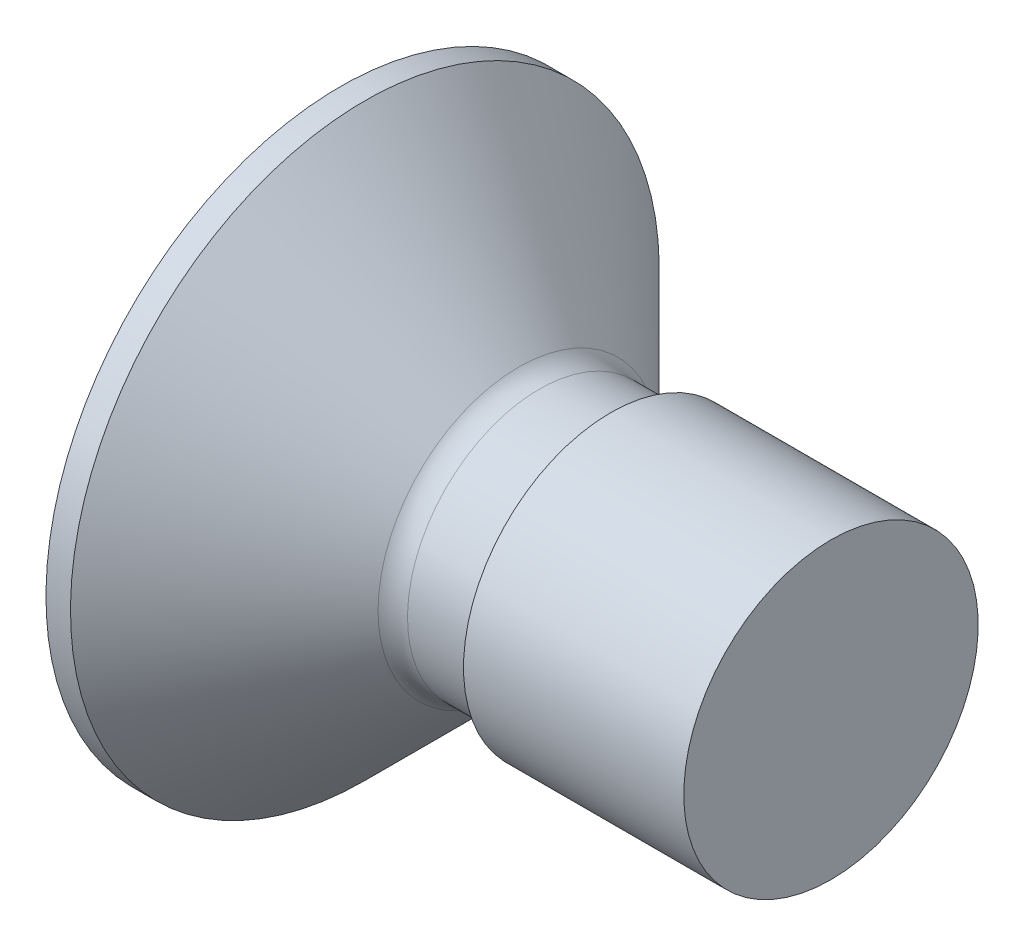
SolidWorks part; units mm, degrees
material "SUS304相当"
ref_plane "Front Plane" through (0, 0, 0) normal (0, 0, 1) x (1, 0, 0)
ref_plane "Top Plane" through (0, 0, 0) normal (0, 1, 0) x (1, 0, 0)
ref_plane "Right Plane" through (0, 0, 0) normal (1, 0, 0) x (0, 0, -1)
sketch "Sketch1" plane through (0, 0, 0) normal (0, 0, 1) x (1, 0, 0)
  line L0 (-1.75, 0) -> (3.25, 0) construction
  line L1 (-1.75, 0) -> (-1.75, 3)
  line L2 (-1.75, 3) -> (-1.5, 3)
  line L3 (-1.5, 3) -> (0.155, 1.345)
  line L4 (0.155, 1.345) -> (1.005, 1.345)
  line L5 (1.005, 1.345) -> (1.005, 1.5)
  line L6 (1.005, 1.5) -> (3.25, 1.5)
  line L7 (3.25, 1.5) -> (3.25, 0)
  line L8 (3.25, 0) -> (-1.75, 0)
  point P8 (0, 1.5)
  point P14 (0.155, 1.345)
  dimension "FIX_1" = 45
  dimension "M" = 3
  dimension "E" = 1.75
  dimension "L" = 5
  dimension "MSM_2" = 2.69
  dimension "A" = 6
  dimension "MSM_3" = 0.85
revolve "Revolve1" add sketch "Sketch1" angle 360 about L0
cosmetic thread "Thread1" parameters "ATD"=2.459
fillet "Fillet1" radius 0.3 1 edges at (0.155, -1.345, 0)
sketch "Sketch2" plane through (-1.75, 0, 0) normal (-1, 0, 0) x (0, 0, 1)
  line L0 (0, 1.8) -> (0, -1.8) construction
  line L1 (-1.8, 0) -> (1.8, 0) construction
  line L3 (-0.4, 1.8) -> (0.4, 1.8)
  line L4 (-0.4, 1.8) -> (-0.4, 1)
  line L6 (0.4, 1.8) -> (0.4, 1)
  line L7 (1, 0.4) -> (1.8, 0.4)
  line L9 (1, -0.4) -> (1.8, -0.4)
  line L10 (1.8, 0.4) -> (1.8, -0.4)
  line L11 (-1, 0.4) -> (-1.8, 0.4)
  line L13 (-1, -0.4) -> (-1.8, -0.4)
  line L14 (-1.8, 0.4) -> (-1.8, -0.4)
  line L16 (-0.4, -1) -> (-0.4, -1.8)
  line L17 (-0.4, -1.8) -> (0.4, -1.8)
  line L18 (0.4, -1) -> (0.4, -1.8)
  arc A0 (-0.4, 1) -> (-1, 0.4) centre (-1, 1) cw
  arc A1 (-0.4, -1) -> (-1, -0.4) centre (-1, -1) ccw
  arc A2 (1, -0.4) -> (0.4, -1) centre (1, -1) ccw
  arc A3 (1, 0.4) -> (0.4, 1) centre (1, 1) cw
  dimension "MSM_6" = 0.6
  dimension "MSM_4" = 0.8
  dimension "MSM_5" = 3.6
extrude "Cut-Extrude1" cut sketch "Sketch2" against normal blind 0.88
